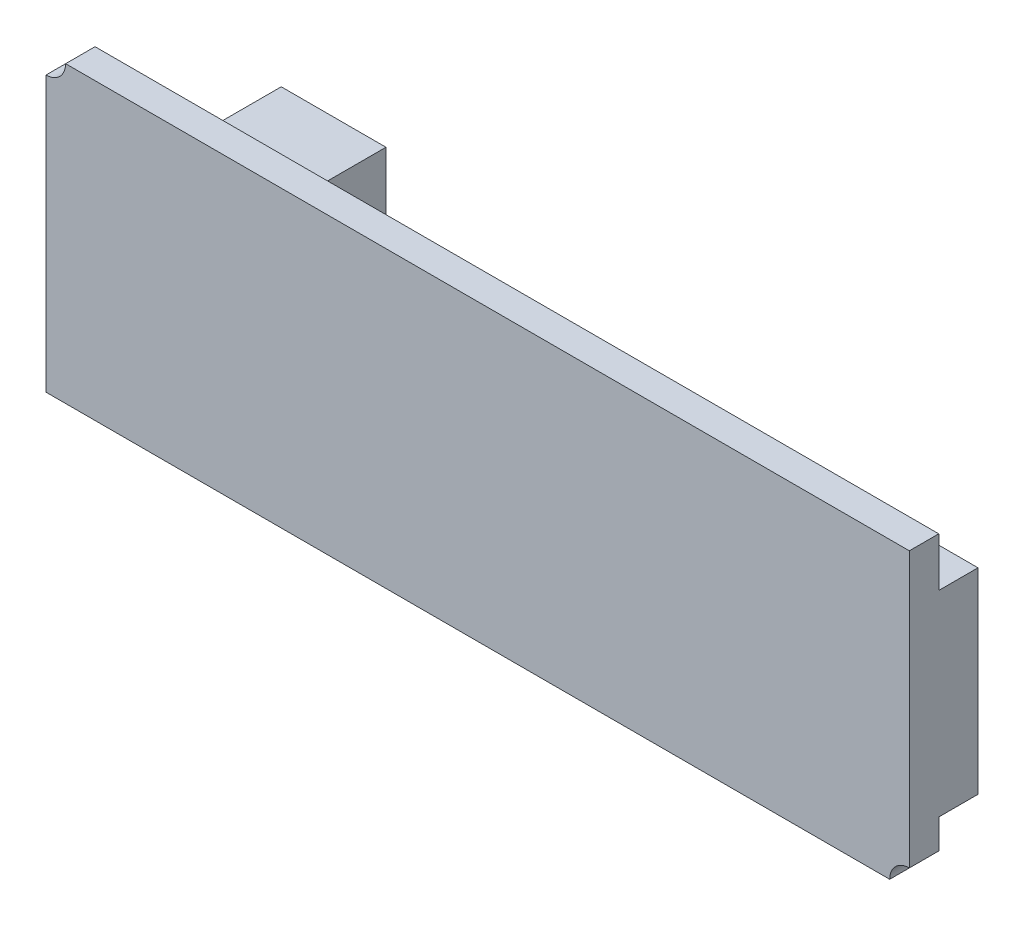
SolidWorks part; units mm, degrees
ref_plane "Plan de face" through (0, 0, 0) normal (0, 0, 1) x (1, 0, 0)
ref_plane "Plan de dessus" through (0, 0, 0) normal (0, 1, 0) x (1, 0, 0)
ref_plane "Plan de droite" through (0, 0, 0) normal (1, 0, 0) x (0, 0, -1)
sketch "Esquisse1" plane through (0, 0, 0) normal (0, 0, 1) x (1, 0, 0)
  line L1 (0, 0) -> (44, 0)
  line L2 (0, 0) -> (0, 15)
  line L3 (0, 15) -> (44, 15)
  line L4 (44, 0) -> (44, 15)
  dimension "D1" = 15
  dimension "D2" = 44
extrude "Boss.-Extru.1" add sketch "Esquisse1" along normal blind 1.5
sketch "Esquisse2" plane through (0, 0, 0) normal (0, 0, -1) x (-1, 0, 0)
  line L0 (-44, 0) -> (-44, 15) construction
  line L1 (-44, 12.5) -> (-38, 12.5)
  line L2 (-44, 12.5) -> (-44, 2.5)
  line L3 (-44, 2.5) -> (-38, 2.5)
  line L4 (-38, 12.5) -> (-38, 2.5)
  line L5 (-44, 15) -> (0, 15) construction
  dimension "D1" = 6
  dimension "D2" = 10
  dimension "D3" = 2.5
extrude "Boss.-Extru.2" add sketch "Esquisse2" along normal blind 2
sketch "Sketch1" plane through (0, 0, 1.5) normal (0, 0, 1) x (1, 0, 0)
  circle A0 centre (44, 0) radius 1
  circle A1 centre (0, 15) radius 1
extrude "Cut-Extrude1" cut sketch "Sketch1" against normal up to next
sketch "Sketch2" plane through (0, 0, 0) normal (0, 0, -1) x (1, 0, 0)
  line L1 (4.4892, -11.9753) -> (9.8259, -11.9753)
  line L2 (4.4892, -11.9753) -> (4.4892, -2.8293)
  line L3 (4.4892, -2.8293) -> (9.8259, -2.8293)
  line L4 (9.8259, -11.9753) -> (9.8259, -2.8293)
extrude "Boss-Extrude1" add sketch "Sketch2" along normal blind 6 contours L2 L1 L4 L3
